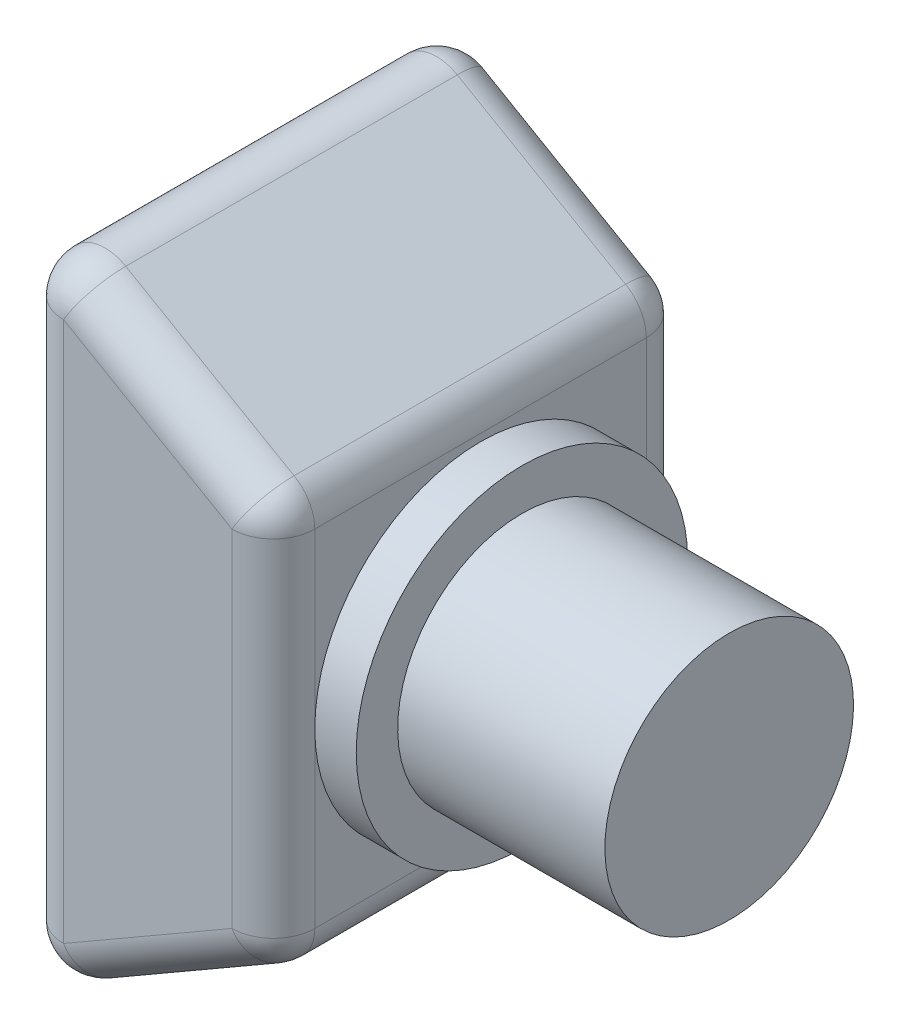
SolidWorks part; units mm, degrees
ref_plane "Ön Düzlem" through (0, 0, 0) normal (0, 0, 1) x (1, 0, 0)
ref_plane "Üst Düzlem" through (0, 0, 0) normal (0, 1, 0) x (1, 0, 0)
ref_plane "Sağ Düzlem" through (0, 0, 0) normal (1, 0, 0) x (0, 0, -1)
sketch "Çizim1" plane through (0, 0, 0) normal (0, 0, 1) x (1, 0, 0)
  line L0 (0, -8.25) -> (0, 8.25)
  line L1 (0, 8.25) -> (6.0622, 4.75)
  line L2 (6.0622, 4.75) -> (6.0622, -4.75)
  line L3 (6.0622, -4.75) -> (0, -8.25)
  line L4 (6.0622, 4.75) -> (6.0622, 7.5979) construction
  point P3 (0, 0)
  dimension "D1" = 60
  dimension "D2" = 7
  dimension "D3" = 9.5
  dimension "D4" = 7
extrude "Yükseklik-Ekstrüzyon1" add sketch "Çizim1" along normal blind 10
fillet "Radyus1" radius 1 4 edges at (0, -8.25, 5) (6.0622, -4.75, 5) (6.0622, 4.75, 5) (0, 8.25, 5)
fillet "Radyus2" radius 1 16 edges at (5.9282, -4.6726, 10) (3.5311, -6.2113, 10) (0.5, -7.384, 10) (0, 0, 10) (0.5, 7.384, 10) (3.5311, 6.2113, 10) (5.9282, 4.6726, 10) (5.9282, -4.6726, 0) (3.5311, -6.2113, 0) (0.5, -7.384, 0) (0, 0, 0) (0.5, 7.384, 0) (3.5311, 6.2113, 0) (5.9282, 4.6726, 0) (6.0622, 0, 10) (6.0622, 0, 0)
sketch "Çizim2" plane through (6.0622, 0, 0) normal (1, 0, 0) x (0, 0, -1)
  line L0 (0, 0) -> (-11.4956, 0) construction
  line L1 (-5, 4.1726) -> (-5, -4.6211) construction
  line L2 (-1, 4.1726) -> (-9, 4.1726) construction
  circle A0 centre (-5, 0) radius 4
  point P7 (-5, 0)
  dimension "D1" = 8
extrude "Yükseklik-Ekstrüzyon2" add sketch "Çizim2" along normal blind 1
sketch "Çizim3" plane through (7.0622, 0, 0) normal (1, 0, 0) x (0, 0, -1)
  circle A0 centre (-5, 0) radius 3
  dimension "D1" = 6
extrude "Yükseklik-Ekstrüzyon3" add sketch "Çizim3" along normal blind 5
